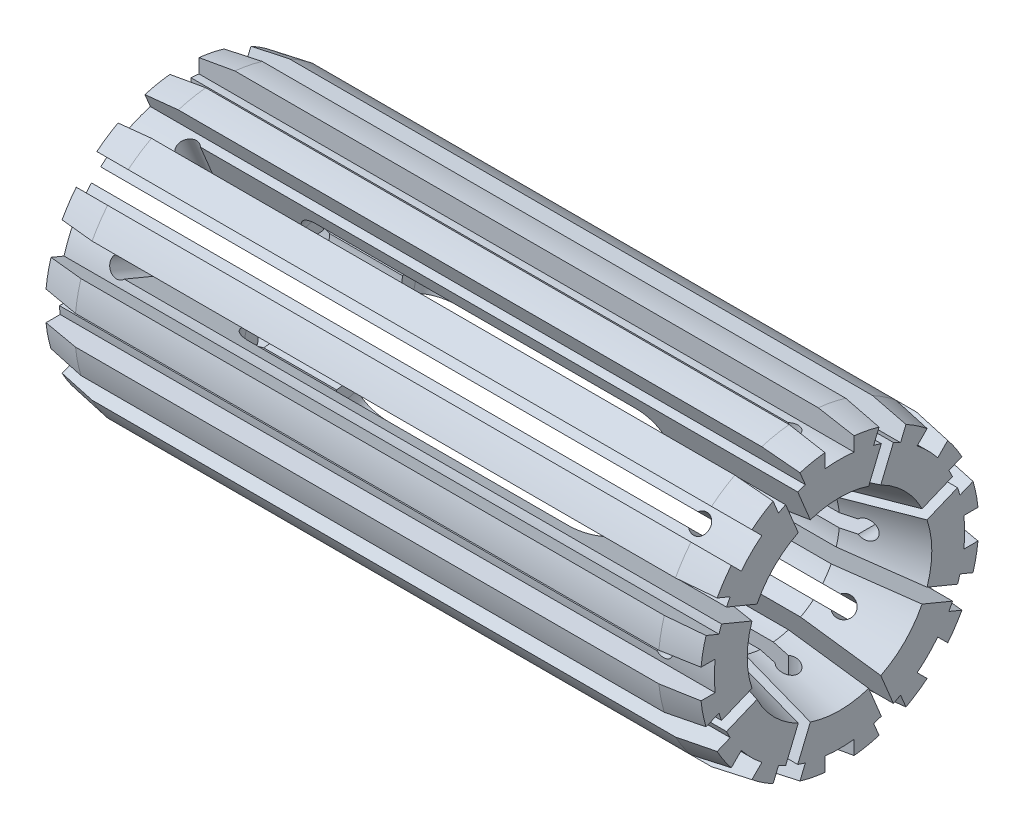
SolidWorks part; units mm, degrees
ref_plane "Alzado" through (0, 0, 0) normal (0, 0, 1) x (1, 0, 0)
ref_plane "Planta" through (0, 0, 0) normal (0, 1, 0) x (1, 0, 0)
ref_plane "Vista lateral" through (0, 0, 0) normal (1, 0, 0) x (0, 0, -1)
sketch "Croquis1" plane through (0, 0, 0) normal (0, 0, 1) x (1, 0, 0)
  line L0 (0, 0) -> (34.3242, 0) construction
  line L1 (15.8948, 12.7) -> (3.1948, 12.7)
  line L2 (3.1948, 12.7) -> (-9.5052, 16.103)
  line L3 (-9.5052, 16.103) -> (-9.5052, 24.2973)
  line L4 (-9.5052, 24.2973) -> (-3.2516, 25.4)
  line L5 (-3.2516, 25.4) -> (98.5413, 25.4)
  line L6 (47.6448, 25.4) -> (47.6448, 14.4015) construction
  line L7 (104.7948, 24.2973) -> (98.5413, 25.4)
  line L8 (104.7948, 16.103) -> (104.7948, 24.2973)
  line L9 (92.0948, 12.7) -> (104.7948, 16.103)
  line L10 (79.3948, 12.7) -> (92.0948, 12.7)
  line L11 (15.8948, 12.7) -> (15.8948, 15.24)
  line L12 (19.7048, 19.05) -> (75.5848, 19.05)
  line L13 (79.3948, 12.7) -> (79.3948, 15.24)
  arc A0 (15.8948, 15.24) -> (19.7048, 19.05) centre (19.7048, 15.24) cw
  arc A1 (79.3948, 15.24) -> (75.5848, 19.05) centre (75.5848, 15.24) ccw
  point P15 (79.3948, 19.05)
  point P19 (15.8948, 19.05)
  point P23 (47.6448, 19.05)
  dimension "D10" = 3.81
  dimension "D1" = 12.7
  dimension "D2" = 12.7
  dimension "D3" = 12.7
  dimension "D4" = 15
  dimension "D5" = 6.35
  dimension "D6" = 10
  dimension "D7" = 12.7
  dimension "D8" = 57.15
  dimension "D9" = 6.35
revolve "Revolución1" add sketch "Croquis1" angle 360 about L0
sketch "Croquis2" plane through (104.7948, 0, 0) normal (1, 0, 0) x (0, 0, -1)
  line L1 (2.54, 21.6958) -> (2.54, 32.4944)
  line L2 (-2.54, 21.6958) -> (-2.54, 32.4944)
  line L3 (-2.54, 32.4944) -> (2.54, 32.4944)
  arc A1 (2.54, 21.6958) -> (-2.54, 21.6958) centre (0, 0) ccw
extrude "Cortar-Extruir4" cut sketch "Croquis2" against normal through all
pattern_circular "MatrizC1" count 16 over 360 about axis through (0, 0, 0) along (1, 0, 0) of "Cortar-Extruir4"
ref_plane "Plano1" through (-9.5052, 20.1812, -8.3593) normal (0, 0.9239, -0.3827) x (1, 0, 0)
sketch "Croquis3" plane through (-9.5052, 20.1812, -8.3593) normal (0, 0.9239, -0.3827) x (1, 0, 0)
  line L0 (123.4735, -1.143) -> (123.4735, 1.143)
  line L1 (10.0814, -1.143) -> (123.4735, -1.143)
  line L2 (10.0814, 1.143) -> (123.4735, 1.143)
  line L3 (0, 2.54) -> (0, -2.54) construction
  arc A0 (10.0814, 1.143) -> (10.0814, -1.143) centre (8.89, 0) ccw
  dimension "D1" = 3.302
  dimension "D2" = 8.89
extrude "Cortar-Extruir5" cut sketch "Croquis3" against normal blind 15.24
pattern_circular "MatrizC2" count 8 over 360 about axis through (0, 0, 0) along (1, 0, 0) of "Cortar-Extruir5"
ref_plane "Plano2" through (104.7948, 21.844, 0) normal (0, 1, 0) x (1, 0, 0)
sketch "Croquis4" plane through (104.7948, 21.844, 0) normal (0, 1, 0) x (1, 0, 0)
  line L0 (-124.9085, -1.143) -> (-124.9085, 1.143)
  line L1 (-10.0814, 1.143) -> (-124.9085, 1.143)
  line L2 (-10.0814, -1.143) -> (-124.9085, -1.143)
  line L3 (0, -2.54) -> (0, 2.54) construction
  arc A0 (-10.0814, -1.143) -> (-10.0814, 1.143) centre (-8.89, 0) ccw
  dimension "D1" = 3.302
  dimension "D2" = 8.89
extrude "Cortar-Extruir6" cut sketch "Croquis4" against normal blind 15.24
pattern_circular "MatrizC3" count 8 over 360 about axis through (0, 0, 0) along (1, 0, 0) of "Cortar-Extruir6"
ref_plane "Plano3" through (-3.2516, 24.9119, -4.9553) normal (0, 0.9808, -0.1951) x (1, 0, 0)
sketch "Croquis5" plane through (-3.2516, 24.9119, -4.9553) normal (0, 0.9808, -0.1951) x (1, 0, 0)
  line L0 (99.8367, 1.5081) -> (2.3744, 1.5081) construction
  text T0 "SOLIDWOKS 2026"
